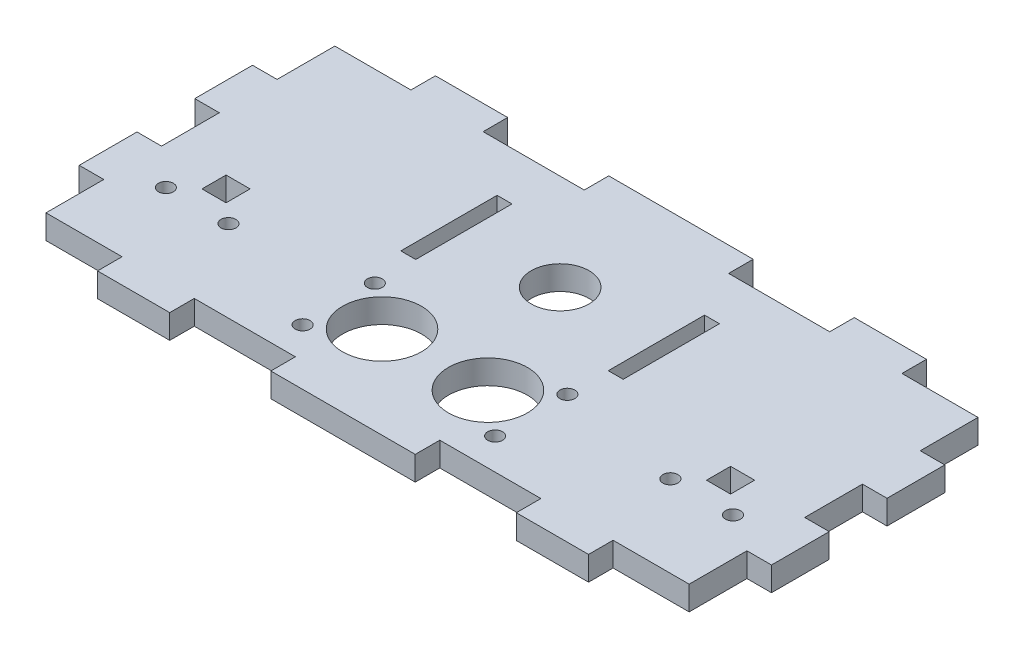
SolidWorks part; units mm, degrees
ref_plane "Front Plane" through (0, 0, 0) normal (0, 0, 1) x (1, 0, 0)
ref_plane "Top Plane" through (0, 0, 0) normal (0, 1, 0) x (1, 0, 0)
ref_plane "Right Plane" through (0, 0, 0) normal (1, 0, 0) x (0, 0, -1)
sketch "Sketch1" plane through (0, 0, 0) normal (0, 1, 0) x (1, 0, 0)
  line L1 (-81.8, -30) -> (-66, -30)
  line L2 (-66, -30) -> (-66, -35.1)
  line L3 (-66, -35.1) -> (-51, -35.1)
  line L4 (-51, -35.1) -> (-51, -30)
  line L5 (-51, -30) -> (-30, -30)
  line L6 (-30, -30) -> (-30, -35.1)
  line L7 (-30, -35.1) -> (0, -35.1)
  line L8 (0, -35.1) -> (0, -30)
  line L9 (0, -30) -> (21, -30)
  line L10 (21, -30) -> (21, -35.1)
  line L11 (21, -35.1) -> (36, -35.1)
  line L12 (36, -35.1) -> (36, -30)
  line L13 (36, -30) -> (51.8, -30)
  line L18 (0, 35.1) -> (0, 30)
  line L19 (36, 30) -> (51.8, 30)
  line L20 (36, 35.1) -> (36, 30)
  line L21 (21, 35.1) -> (36, 35.1)
  line L22 (21, 30) -> (21, 35.1)
  line L23 (0, 30) -> (21, 30)
  line L24 (-30, 35.1) -> (0, 35.1)
  line L25 (-30, 30) -> (-30, 35.1)
  line L26 (-51, 30) -> (-30, 30)
  line L27 (-51, 35.1) -> (-51, 30)
  line L28 (-66, 35.1) -> (-51, 35.1)
  line L29 (-66, 30) -> (-66, 35.1)
  line L30 (-81.8, 30) -> (-66, 30)
  line L31 (-81.8, 30) -> (-81.8, 18)
  line L32 (-81.8, 18) -> (-86.9, 18)
  line L33 (-86.9, 18) -> (-86.9, 6)
  line L34 (-86.9, 6) -> (-81.8, 6)
  line L35 (-81.8, 6) -> (-81.8, -6)
  line L36 (-81.8, -6) -> (-86.9, -6)
  line L37 (-86.9, -6) -> (-86.9, -18)
  line L38 (-86.9, -18) -> (-81.8, -18)
  line L39 (-81.8, -18) -> (-81.8, -30)
  line L40 (-15, 35.1) -> (-15, 23.7245) construction
  line L41 (51.8, 18) -> (56.9, 18)
  line L42 (51.8, -18) -> (51.8, -30)
  line L43 (56.9, -18) -> (51.8, -18)
  line L44 (56.9, -6) -> (56.9, -18)
  line L45 (51.8, -6) -> (56.9, -6)
  line L46 (51.8, 6) -> (51.8, -6)
  line L47 (56.9, 6) -> (51.8, 6)
  line L48 (56.9, 18) -> (56.9, 6)
  line L49 (51.8, 30) -> (51.8, 18)
  line L50 (8.1, 20) -> (5, 20)
  line L51 (8.1, 20) -> (8.1, 0)
  line L52 (8.1, 0) -> (5, 0)
  line L53 (5, 20) -> (5, 0)
  line L54 (-35, 20) -> (-38.1, 20)
  line L55 (-35, 20) -> (-35, 0)
  line L56 (-35, 0) -> (-38.1, 0)
  line L57 (-38.1, 20) -> (-38.1, 0)
  line L58 (-69.9, -4.5) -> (-64.9, -4.5)
  line L59 (-69.9, -4.5) -> (-69.9, -9.5)
  line L60 (-69.9, -9.5) -> (-64.9, -9.5)
  line L61 (-64.9, -4.5) -> (-64.9, -9.5)
  line L62 (39.9, -9.5) -> (34.9, -9.5)
  line L63 (34.9, -4.5) -> (34.9, -9.5)
  line L64 (39.9, -4.5) -> (34.9, -4.5)
  line L65 (39.9, -4.5) -> (39.9, -9.5)
  circle A0 centre (-4, -16) radius 8.2
  circle A1 centre (-26, -16) radius 8.2
  circle A2 centre (-15, 10) radius 6
  circle A3 centre (5, -8.5) radius 1.55
  circle A4 centre (5, -23.5) radius 1.55
  circle A5 centre (-35, -8.5) radius 1.55
  circle A6 centre (-35, -23.5) radius 1.55
  circle A7 centre (-73.9, -13) radius 1.55
  circle A8 centre (-60.9, -13) radius 1.55
  circle A9 centre (30.9, -13) radius 1.55
  circle A10 centre (43.9, -13) radius 1.55
  point P69 (-86.9, -12)
  point P76 (-67.4, -9.5)
  dimension "D37" = 16.4
  dimension "D38" = 16.4
  dimension "D42" = 12
  dimension "D52" = 3.1
  dimension "D55" = 15
  dimension "D56" = 40
  dimension "D57" = 5
  dimension "D59" = 13
  dimension "D2" = 15.8
  dimension "D3" = 5.1
  dimension "D4" = 15
  dimension "D5" = 5.1
  dimension "D6" = 21
  dimension "D7" = 5.1
  dimension "D8" = 30
  dimension "D9" = 5.1
  dimension "D10" = 21
  dimension "D11" = 5.1
  dimension "D12" = 15
  dimension "D13" = 5.1
  dimension "D14" = 15.8
  dimension "D15" = 60
  dimension "D16" = 15.8
  dimension "D17" = 5.1
  dimension "D18" = 15
  dimension "D19" = 5.1
  dimension "D20" = 21
  dimension "D21" = 5.1
  dimension "D22" = 30
  dimension "D23" = 5.1
  dimension "D24" = 21
  dimension "D25" = 5.1
  dimension "D26" = 15
  dimension "D27" = 5.1
  dimension "D28" = 15.8
  dimension "D29" = 60
  dimension "D30" = 12
  dimension "D31" = 5.1
  dimension "D32" = 12
  dimension "D33" = 5.1
  dimension "D34" = 12
  dimension "D35" = 12
  dimension "D36" = 12
  dimension "D39" = 22
  dimension "D40" = 14
  dimension "D41" = 60.9
  dimension "D43" = 71.9
  dimension "D44" = 3.1
  dimension "D45" = 20
  dimension "D46" = 20
  dimension "D47" = 10
  dimension "D48" = 40
  dimension "D49" = 3.1
  dimension "D50" = 20
  dimension "D51" = 20
  dimension "D53" = 21.5
  dimension "D54" = 9
  dimension "D58" = 13
  dimension "D60" = 5
  dimension "D61" = 5
  dimension "D62" = 3.5
  dimension "D63" = 4
extrude "Boss-Extrude1" add sketch "Sketch1" along normal blind 5
